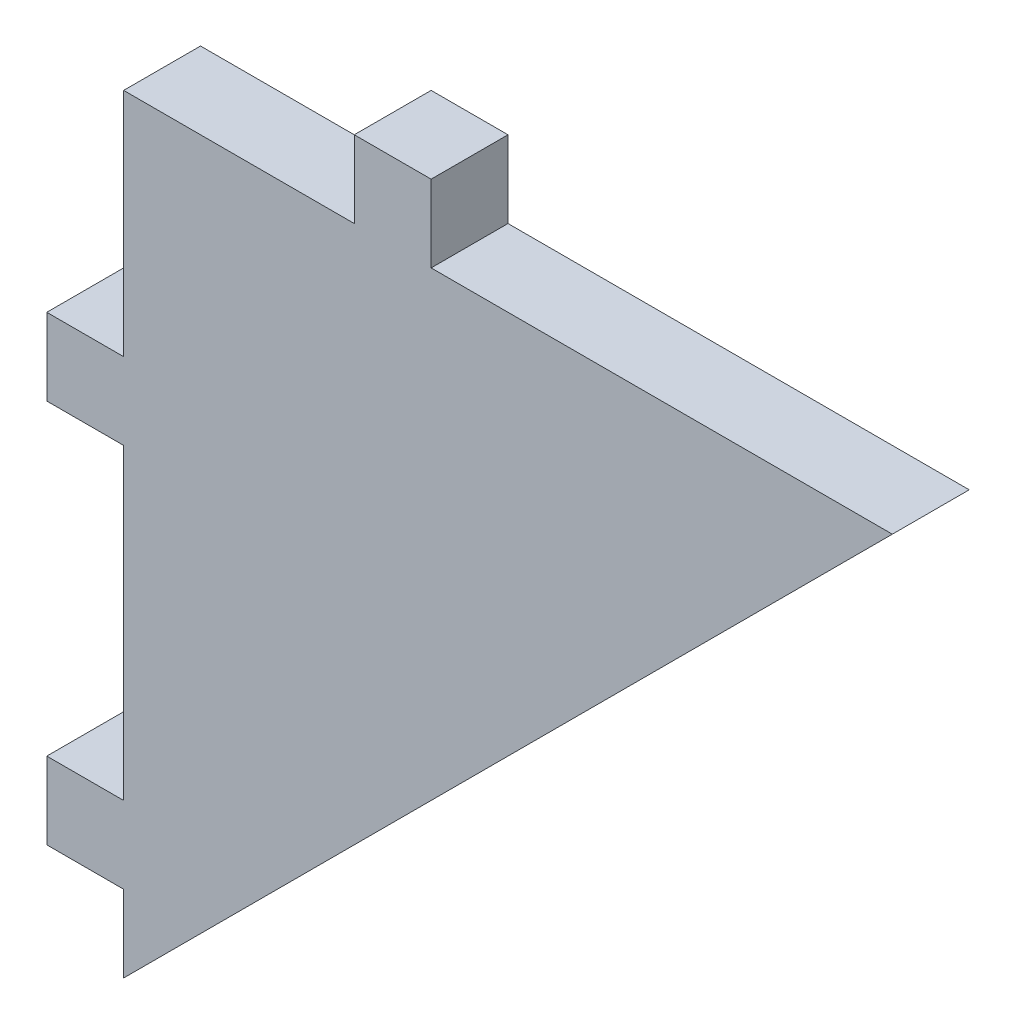
SolidWorks part; units mm, degrees
ref_plane "Front Plane" through (0, 0, 0) normal (0, 0, 1) x (1, 0, 0)
ref_plane "Top Plane" through (0, 0, 0) normal (0, 1, 0) x (1, 0, 0)
ref_plane "Right Plane" through (0, 0, 0) normal (1, 0, 0) x (0, 0, -1)
sketch "Sketch1" plane through (0, 0, 0) normal (0, 0, 1) x (1, 0, 0)
  line L0 (0, 0) -> (0, 5)
  line L1 (0, 5) -> (-5, 5)
  line L2 (-5, 5) -> (-5, 10)
  line L3 (-5, 10) -> (0, 10)
  line L4 (0, 10) -> (0, 30)
  line L5 (0, 30) -> (-5, 30)
  line L6 (-5, 30) -> (-5, 35)
  line L7 (-5, 35) -> (0, 35)
  line L8 (0, 35) -> (0, 50)
  line L9 (0, 50) -> (15, 50)
  line L10 (15, 50) -> (15, 55)
  line L11 (15, 55) -> (20, 55)
  line L12 (20, 55) -> (20, 50)
  line L13 (20, 50) -> (50, 50)
  line L14 (50, 50) -> (0, 0)
  line L15 (0, 0) -> (50, 0) construction
  line L16 (50, 0) -> (50, 50) construction
  dimension "D1" = 45
  dimension "D2" = 50
  dimension "D3" = 5
  dimension "D4" = 20
  dimension "D5" = 5
  dimension "D6" = 5
  dimension "D7" = 15
extrude "Extrude1" add sketch "Sketch1" along normal blind 5
